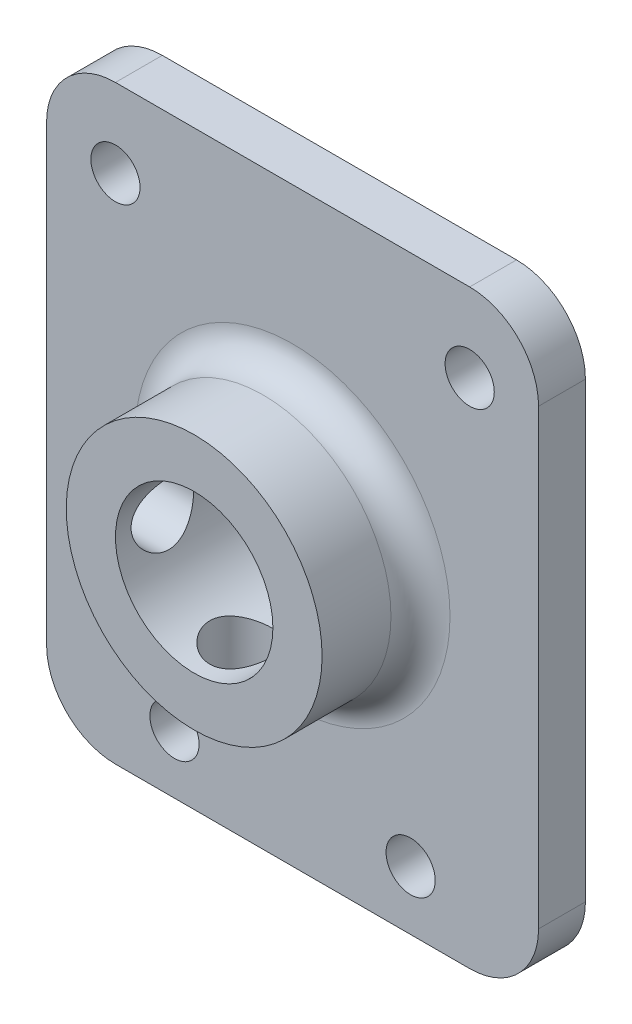
SolidWorks part; units mm, degrees
ref_plane "Alzado" through (0, 0, 0) normal (0, 0, 1) x (1, 0, 0)
ref_plane "Planta" through (0, 0, 0) normal (0, 1, 0) x (1, 0, 0)
ref_plane "Vista lateral" through (0, 0, 0) normal (1, 0, 0) x (0, 0, -1)
sketch "Croquis1" plane through (0, 0, 0) normal (0, 0, 1) x (1, 0, 0)
  line L1 (-25, 30) -> (25, 30)
  line L2 (-25, 30) -> (-25, -30)
  line L3 (-25, -30) -> (25, -30)
  line L4 (25, 30) -> (25, -30)
  line L5 (-25, 30) -> (25, -30) construction
  line L6 (-25, -30) -> (25, 30) construction
  point P0 (0, 0)
  dimension "D1" = 50
  dimension "D2" = 60
extrude "Saliente-Extruir1" add sketch "Croquis1" along normal blind 4.7625
sketch "Croquis2" plane through (0, 0, 4.7625) normal (0, 0, 1) x (1, 0, 0)
  circle A0 centre (0, 0) radius 13
  dimension "D1" = 26
extrude "Saliente-Extruir2" add sketch "Croquis2" along normal blind 10
sketch "Croquis7" plane through (0, 0, 0) normal (0, 0, -1) x (-1, 0, 0)
  circle A0 centre (0, 0) radius 21 construction
  circle A1 centre (0, 0) radius 18.9 construction
  dimension "D1" = 42
  dimension "D2" = 37.8
sketch "Croquis3" plane through (0, 0, 14.7625) normal (0, 0, 1) x (1, 0, 0)
  circle A0 centre (0, 0) radius 8
  dimension "D1" = 16
extrude "Cortar-Extruir1" cut sketch "Croquis3" against normal through all
sketch "Croquis4" plane through (0, 0, 4.7625) normal (0, 0, 1) x (1, 0, 0)
  line L0 (25, -30) -> (25, 30) construction
  line L1 (25, 30) -> (-25, 30) construction
  line L2 (-25, -30) -> (25, -30) construction
  line L3 (0, 0) -> (0, 43.894) construction
  circle A0 centre (18, 22) radius 2.5
  circle A1 centre (12, -24) radius 2.5
  circle A2 centre (-12, -24) radius 2.5
  circle A3 centre (-18, 22) radius 2.5
  point P15 (-2.5, 2.5)
  dimension "D1" = 5
  dimension "D2" = 7
  dimension "D3" = 8
  dimension "D4" = 5
  dimension "D5" = 6
  dimension "D6" = 13
extrude "Cortar-Extruir2" cut sketch "Croquis4" against normal through all
fillet "Redondeo1" radius 3 1 edges at (13, 0, 4.7625)
fillet "Redondeo2" radius 7 4 edges at (-25, -30, 2.3813) (25, -30, 2.3813) (25, 30, 2.3813) (-25, 30, 2.3813)
sketch "Croquis5" plane through (0, 0, 0) normal (0, 1, 0) x (1, 0, 0)
  line L0 (0, 0) -> (0, -15.1377) construction
  circle A0 centre (0, -10) radius 3.175
  dimension "D1" = 6.35
  dimension "D2" = 10
extrude "Cortar-Extruir3" cut sketch "Croquis5" against normal through all
sketch "Croquis6" plane through (0, 0, 0) normal (1, 0, 0) x (0, 0, -1)
  line L0 (0, 0) -> (-18.9731, 0) construction
  circle A0 centre (-10, 0) radius 3.175
  dimension "D1" = 6.35
  dimension "D2" = 10
extrude "Cortar-Extruir4" cut sketch "Croquis6" against normal through all
